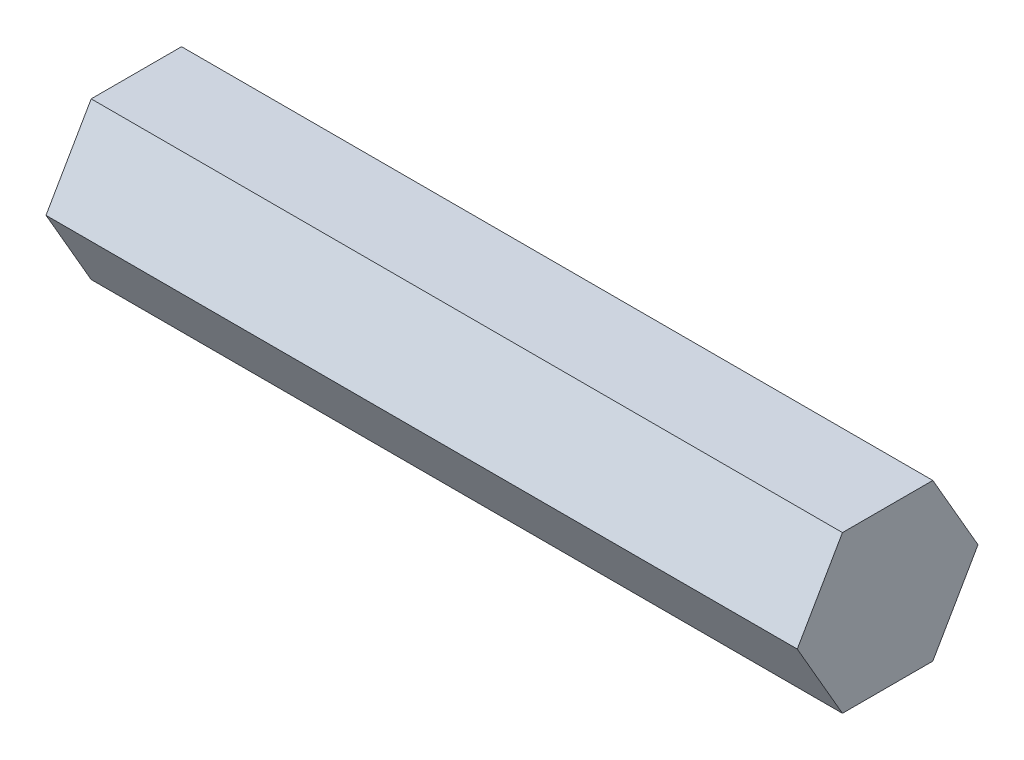
SolidWorks part; units mm, degrees
ref_plane "Front Plane" through (0, 0, 0) normal (0, 0, 1) x (1, 0, 0)
ref_plane "Top Plane" through (0, 0, 0) normal (0, 1, 0) x (1, 0, 0)
ref_plane "Right Plane" through (0, 0, 0) normal (1, 0, 0) x (0, 0, -1)
sketch "Sketch1" plane through (0, 0, 0) normal (1, 0, 0) x (0, 0, -1)
  line L1 (7.3323, 0) -> (3.6662, 6.35)
  line L2 (3.6662, 6.35) -> (-3.6662, 6.35)
  line L3 (-3.6662, 6.35) -> (-7.3323, 0)
  line L4 (-7.3323, 0) -> (-3.6662, -6.35)
  line L5 (-3.6662, -6.35) -> (3.6662, -6.35)
  line L6 (3.6662, -6.35) -> (7.3323, 0)
  circle A0 centre (0, 0) radius 6.35 construction
  dimension "D1" = 12.7
extrude "Boss-Extrude1" add sketch "Sketch1" along normal blind 60.96
